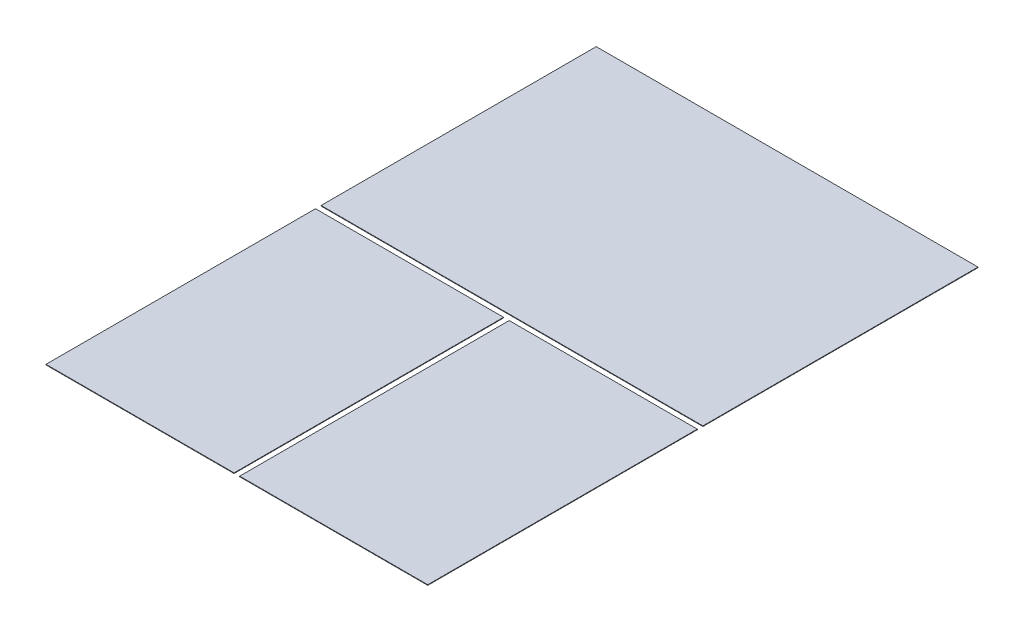
SolidWorks part; units mm, degrees
ref_plane "Front Plane" through (0, 0, 0) normal (0, 0, 1) x (1, 0, 0)
ref_plane "Top Plane" through (0, 0, 0) normal (0, 1, 0) x (1, 0, 0)
ref_plane "Right Plane" through (0, 0, 0) normal (1, 0, 0) x (0, 0, -1)
sketch "Sketch1" plane through (0, 0, 0) normal (0, 1, 0) x (1, 0, 0)
  line L0 (1847.3035, 25.221) -> (-1552.6965, 25.221)
  line L1 (1847.3035, 25.221) -> (1847.3035, 2475.221)
  line L2 (1847.3035, 2475.221) -> (-1552.6965, 2475.221)
  line L3 (-1552.6965, 25.221) -> (-1552.6965, 2475.221)
  line L4 (1847.3035, 25.221) -> (-1552.6965, 2475.221) construction
  line L5 (1847.3035, 2475.221) -> (-1552.6965, 25.221) construction
  line L6 (172.3035, -24.779) -> (1847.3035, -24.779)
  line L7 (-1552.6965, 25.221) -> (1847.3035, 25.221)
  line L9 (-1552.6965, -24.779) -> (122.3035, -24.779)
  line L11 (-1552.6965, 25.221) -> (1847.3035, -24.779) construction
  line L12 (-1552.6965, -24.779) -> (1847.3035, 25.221) construction
  line L13 (-1552.6965, -24.779) -> (122.3035, -24.779)
  line L14 (-1552.6965, -24.779) -> (-1552.6965, -2424.779)
  line L15 (-1552.6965, -2424.779) -> (122.3035, -2424.779)
  line L16 (122.3035, -24.779) -> (122.3035, -2424.779)
  line L17 (-1552.6965, -24.779) -> (122.3035, -2424.779) construction
  line L18 (-1552.6965, -2424.779) -> (122.3035, -24.779) construction
  line L19 (1847.3035, -24.779) -> (172.3035, -24.779)
  line L20 (1847.3035, -24.779) -> (1847.3035, -2424.779)
  line L21 (1847.3035, -2424.779) -> (172.3035, -2424.779)
  line L22 (172.3035, -24.779) -> (172.3035, -2424.779)
  line L23 (1847.3035, -24.779) -> (172.3035, -2424.779) construction
  line L24 (1847.3035, -2424.779) -> (172.3035, -24.779) construction
  point P0 (147.3035, 1250.221)
  point P7 (147.3035, 0.221)
  point P11 (-715.1965, -1224.779)
  point P15 (1009.8035, -1224.779)
  dimension "D1" = 3400
  dimension "D2" = 2450
  dimension "D3" = 50
  dimension "D4" = 1675
  dimension "D5" = 2400
  dimension "D6" = 1675
  dimension "D7" = 50
extrude "Boss-Extrude1" add sketch "Sketch1" along normal blind 5 contours L3 L0 L1 L2 | L6 L22 L21 L20 | L16 L9 L14 L15
